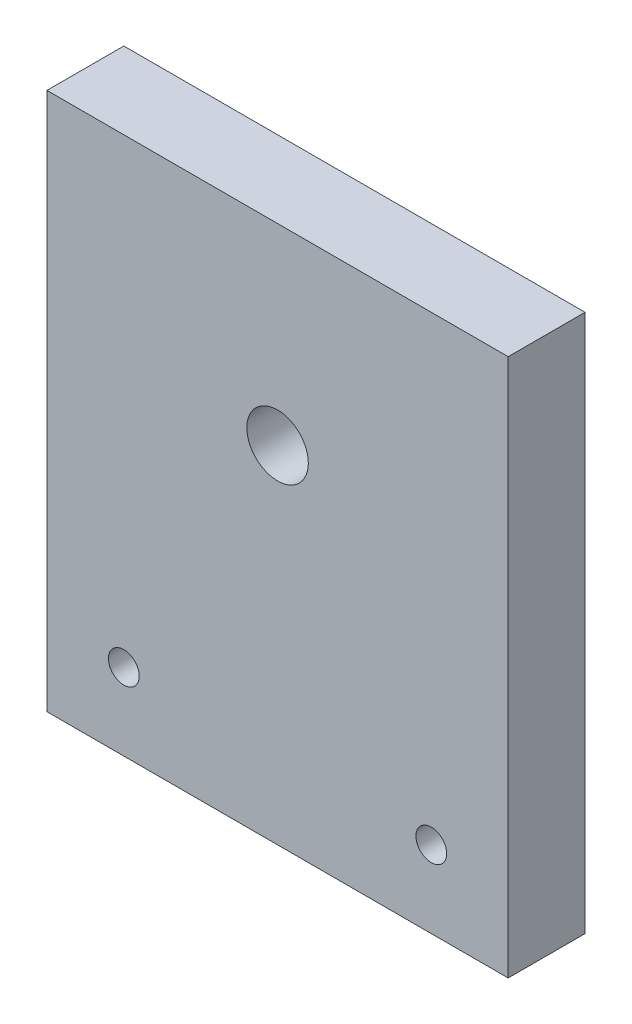
SolidWorks part; units mm, degrees
ref_plane "Front Plane" through (0, 0, 0) normal (0, 0, 1) x (1, 0, 0)
ref_plane "Top Plane" through (0, 0, 0) normal (0, 1, 0) x (1, 0, 0)
ref_plane "Right Plane" through (0, 0, 0) normal (1, 0, 0) x (0, 0, -1)
sketch "Sketch1" plane through (0, 0, 0) normal (0, 0, 1) x (1, 0, 0)
  line L0 (-30, -25) -> (30, -25) construction
  line L1 (-30, 25) -> (30, 25)
  line L2 (-30, 25) -> (-30, -45)
  line L3 (-30, -45) -> (30, -45)
  line L4 (30, 25) -> (30, -45)
  line L5 (-30, 25) -> (30, -45) construction
  line L6 (-30, -45) -> (30, 25) construction
  circle A0 centre (-20, -35) radius 2
  circle A1 centre (20, -35) radius 2
  circle A2 centre (0, 0) radius 4
  circle A3 centre (0, 0) radius 11
  point P0 (0, -10)
  dimension "D3" = 4
  dimension "D4" = 4
  dimension "D9" = 8
  dimension "D11" = 22
  dimension "D1" = 60
  dimension "D2" = 70
  dimension "D5" = 10
  dimension "D6" = 10
  dimension "D7" = 10
  dimension "D8" = 10
  dimension "D10" = 45
  dimension "D12" = 20
extrude "Boss-Extrude1" add sketch "Sketch1" along normal blind 10 contours A3 A2 | L4 L1 L2 L3 A3 A1 A0
